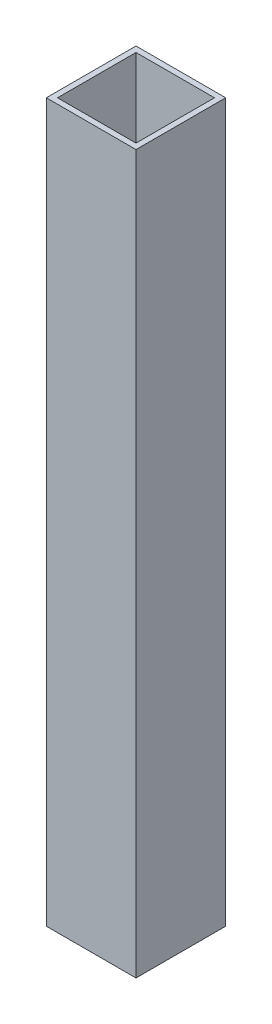
SolidWorks part; units mm, degrees
material "6061 Alloy"
ref_plane "Front Plane" through (0, 0, 0) normal (0, 0, 1) x (1, 0, 0)
ref_plane "Top Plane" through (0, 0, 0) normal (0, 1, 0) x (1, 0, 0)
ref_plane "Right Plane" through (0, 0, 0) normal (1, 0, 0) x (0, 0, -1)
sketch "Sketch1" plane through (0, 0, 0) normal (0, 1, 0) x (1, 0, 0)
  line L1 (-12.7, -12.7) -> (12.7, -12.7)
  line L2 (-12.7, -12.7) -> (-12.7, 12.7)
  line L3 (-12.7, 12.7) -> (12.7, 12.7)
  line L4 (12.7, -12.7) -> (12.7, 12.7)
  line L7 (-11.1125, -11.1125) -> (11.1125, -11.1125)
  line L8 (-11.1125, -11.1125) -> (-11.1125, 11.1125)
  line L9 (-11.1125, 11.1125) -> (11.1125, 11.1125)
  line L10 (11.1125, -11.1125) -> (11.1125, 11.1125)
  point P6 (0, 0)
  dimension "D1" = 25.4
  dimension "D2" = 25.4
  dimension "D3" = 1.5875
  dimension "D4" = 1.5875
  dimension "D5" = 1.5875
extrude "Boss-Extrude1" add sketch "Sketch1" along normal blind 203.2
